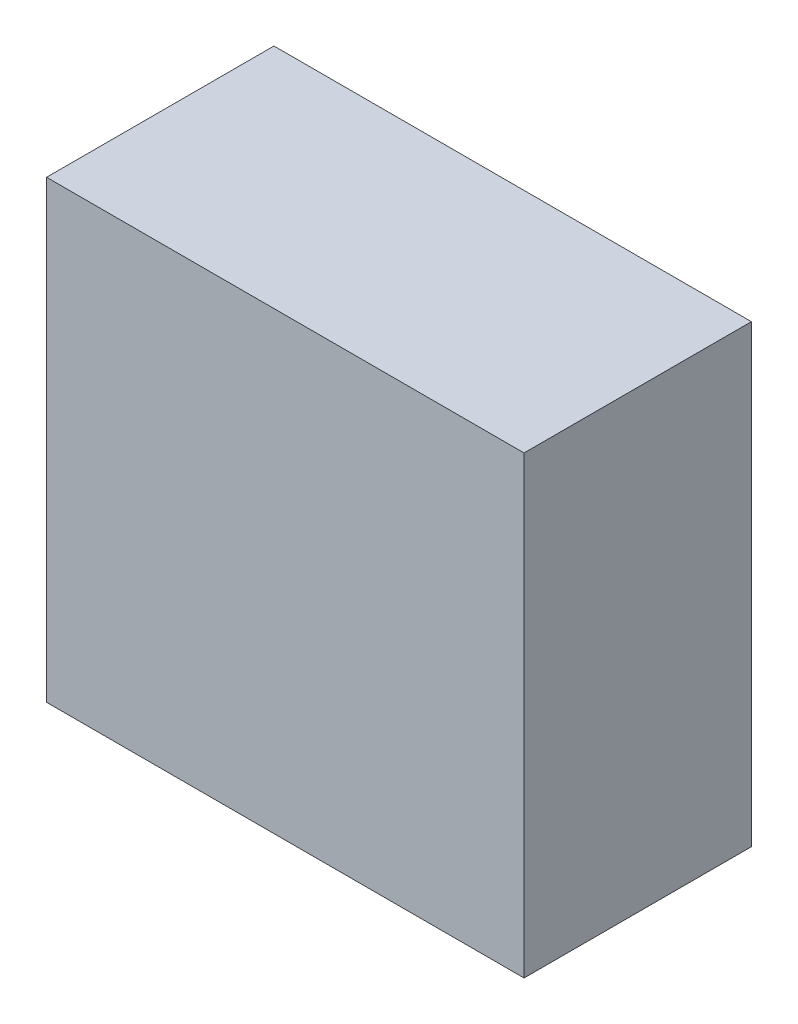
SolidWorks part; units mm, degrees
ref_plane "Front Plane" through (0, 0, 0) normal (0, 0, 1) x (1, 0, 0)
ref_plane "Top Plane" through (0, 0, 0) normal (0, 1, 0) x (1, 0, 0)
ref_plane "Right Plane" through (0, 0, 0) normal (1, 0, 0) x (0, 0, -1)
sketch "Sketch1" plane through (0, 0, 0) normal (0, 0, 1) x (1, 0, 0)
  line L1 (-21, -20) -> (21, -20)
  line L2 (-21, -20) -> (-21, 20)
  line L3 (-21, 20) -> (21, 20)
  line L4 (21, -20) -> (21, 20)
  line L5 (-21, -20) -> (21, 20) construction
  line L6 (-21, 20) -> (21, -20) construction
  point P0 (0, 0)
  dimension "D1" = 42
  dimension "D2" = 40
extrude "Boss-Extrude1" add sketch "Sketch1" along normal blind 20 contours L2 L1 L4 L3
